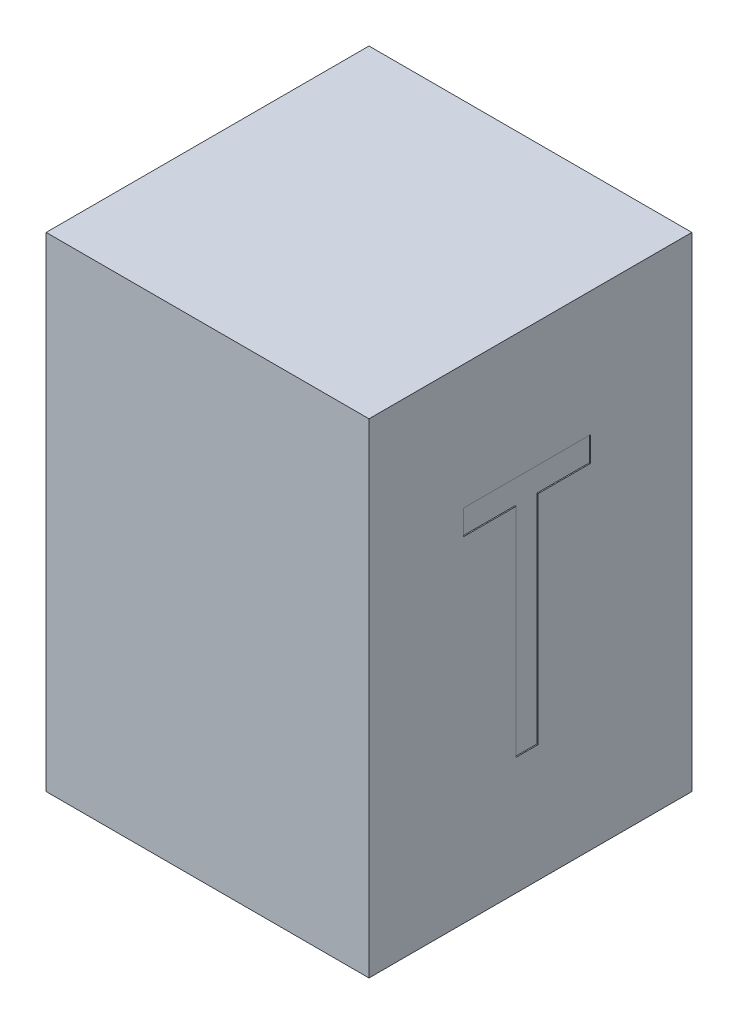
SolidWorks part; units mm, degrees
ref_plane "Front Plane" through (0, 0, 0) normal (0, 0, 1) x (1, 0, 0)
ref_plane "Top Plane" through (0, 0, 0) normal (0, 1, 0) x (1, 0, 0)
ref_plane "Right Plane" through (0, 0, 0) normal (1, 0, 0) x (0, 0, -1)
sketch "Sketch1" plane through (0, 0, 0) normal (0, 1, 0) x (1, 0, 0)
  line L1 (0, 0) -> (76.2, 0)
  line L2 (0, 0) -> (0, -76.2)
  line L3 (0, -76.2) -> (76.2, -76.2)
  line L4 (76.2, 0) -> (76.2, -76.2)
  dimension "D1" = 76.2
  dimension "D2" = 76.2
extrude "Boss-Extrude1" add sketch "Sketch1" along normal blind 114.3
sketch "Sketch2" plane through (76.2, 0, 0) normal (1, 0, 0) x (0, 0, -1)
  text T0 "T" font "Century Gothic" height 57.15
extrude "Cut-Extrude1" cut sketch "Sketch2" against normal blind 0.254
